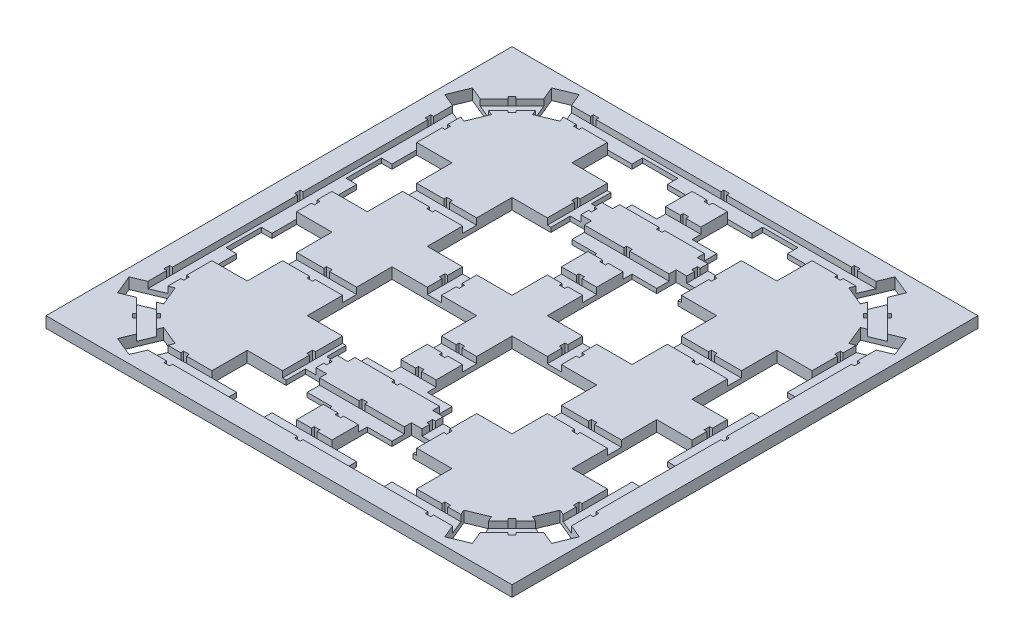
SolidWorks part; units mm, degrees
material "轻木"
ref_plane "前视基准面" through (0, 0, 0) normal (0, 0, 1) x (1, 0, 0)
ref_plane "上视基准面" through (0, 0, 0) normal (0, 1, 0) x (1, 0, 0)
ref_plane "右视基准面" through (0, 0, 0) normal (1, 0, 0) x (0, 0, -1)
sketch "草图1" plane through (0, 0, 0) normal (0, 1, 0) x (1, 0, 0)
  line L1 (-330, 330) -> (330, 330)
  line L2 (-330, 330) -> (-330, -330)
  line L3 (-330, -330) -> (330, -330)
  line L4 (330, 330) -> (330, -330)
  line L5 (-330, 330) -> (330, -330) construction
  line L6 (-330, -330) -> (330, 330) construction
  point P0 (0, 0)
  dimension "D1" = 660
  dimension "D2" = 660
extrude "凸台-拉伸1" add sketch "草图1" along normal blind 15.5
sketch "草图2" plane through (0, 15.5, 0) normal (0, 1, 0) x (1, 0, 0)
  line L0 (0, 0) -> (50000, 0) construction
  line L1 (-290, 290) -> (290, 290) construction
  line L2 (-290, 290) -> (-290, -290) construction
  line L3 (-290, -290) -> (290, -290) construction
  line L4 (290, 290) -> (290, -290) construction
  line L5 (-290, 290) -> (290, -290) construction
  line L6 (-290, -290) -> (290, 290) construction
  line L7 (0, 0) -> (0, 50000) construction
  line L8 (-290, 227.8579) -> (-227.8579, 290) construction
  line L9 (-280, 223.7157) -> (-280, 95)
  line L10 (-223.7157, 280) -> (-95, 280)
  line L11 (-280, 223.7157) -> (-223.7157, 280)
  line L12 (-300, 212) -> (-300, -232)
  line L13 (-212, 300) -> (212, 300)
  line L14 (-300, 232) -> (-232, 300)
  line L15 (-297.0711, 234.9289) -> (-234.9289, 297.0711) construction
  line L16 (-282.9289, 220.7868) -> (-220.7868, 282.9289) construction
  line L17 (280, 223.7157) -> (223.7157, 280)
  line L18 (300, 232) -> (232, 300)
  line L19 (280, 223.7157) -> (280, 95)
  line L20 (300, 212) -> (300, -232)
  line L21 (280, -223.7157) -> (223.7157, -280)
  line L22 (-300, 300) -> (290, 300) construction
  line L23 (-300, 300) -> (-300, -290) construction
  line L24 (-280, 280) -> (290, 280) construction
  line L25 (-280, 280) -> (-280, -290) construction
  line L26 (300, -232) -> (232, -300)
  line L27 (-232, -300) -> (232, -300)
  line L28 (-300, -232) -> (-232, -300)
  line L29 (-223.7157, -280) -> (-95, -280)
  line L30 (-280, -223.7157) -> (-223.7157, -280)
  line L31 (-95, 280) -> (-95, 95)
  line L32 (-75, 280) -> (-75, 242.5)
  line L33 (75, 280) -> (75, 242.5)
  line L34 (95, 280) -> (95, 95)
  line L35 (-280, -95) -> (-95, -95)
  line L36 (-280, -75) -> (-95, -75)
  line L37 (-280, 75) -> (-95, 75)
  line L38 (-280, 95) -> (-95, 95)
  line L39 (-75, 95) -> (75, 95)
  line L40 (-95, 75) -> (-95, -75)
  line L41 (-75, 75) -> (75, 75)
  line L42 (-75, 75) -> (-75, -75)
  line L43 (75, 75) -> (75, -75)
  line L44 (95, 95) -> (280, 95)
  line L45 (95, 75) -> (95, -75)
  line L46 (95, 75) -> (280, 75)
  line L47 (-75, -75) -> (75, -75)
  line L48 (-95, -95) -> (-95, -280)
  line L49 (-75, -95) -> (75, -95)
  line L50 (-75, -95) -> (-75, -132.5)
  line L51 (75, -95) -> (75, -132.5)
  line L52 (95, -75) -> (280, -75)
  line L53 (95, -95) -> (95, -280)
  line L54 (95, -95) -> (280, -95)
  line L55 (-75, 280) -> (75, 280)
  line L56 (95, 280) -> (223.7157, 280)
  line L57 (-280, 75) -> (-280, -75)
  line L58 (-280, -95) -> (-280, -223.7157)
  line L59 (-75, -280) -> (75, -280)
  line L60 (95, -280) -> (223.7157, -280)
  line L61 (280, -95) -> (280, -223.7157)
  line L62 (280, 75) -> (280, -75)
  line L63 (-75, 242.5) -> (75, 242.5)
  line L64 (-75, 212.5) -> (75, 212.5)
  line L65 (-75, 162.5) -> (75, 162.5)
  line L66 (-75, 132.5) -> (75, 132.5)
  line L67 (-75, -132.5) -> (75, -132.5)
  line L68 (-75, -162.5) -> (75, -162.5)
  line L69 (-75, -212.5) -> (75, -212.5)
  line L70 (-75, -242.5) -> (75, -242.5)
  line L71 (-75, -162.5) -> (-75, -212.5)
  line L72 (75, -162.5) -> (75, -212.5)
  line L73 (-75, -242.5) -> (-75, -280)
  line L74 (75, -242.5) -> (75, -280)
  line L75 (-75, 212.5) -> (-75, 162.5)
  line L76 (-75, 132.5) -> (-75, 95)
  line L77 (75, 212.5) -> (75, 162.5)
  line L78 (75, 132.5) -> (75, 95)
  line L79 (-212, 300) -> (-232, 300)
  line L80 (-300, 232) -> (-300, 212)
  line L81 (212, 300) -> (232, 300)
  line L82 (300, 232) -> (300, 212)
  arc A0 (-212, 300) -> (-232, 300) centre (-222, 300) ccw construction
  arc A1 (-300, 212) -> (-300, 232) centre (-300, 222) cw construction
  arc A2 (300, 212) -> (300, 232) centre (300, 222) ccw construction
  arc A3 (212, 300) -> (232, 300) centre (222, 300) cw construction
  circle A4 centre (-300, -222) radius 10 construction
  circle A5 centre (-222, -300) radius 10 construction
  circle A6 centre (300, -222) radius 10 construction
  circle A7 centre (222, -300) radius 10 construction
  point P0 (0, 0)
  dimension "D12" = 20
  dimension "D1" = 45
  dimension "D2" = 10
  dimension "D4" = 464
  dimension "D5" = 600
  dimension "D6" = 20
  dimension "D7" = 185
  dimension "D8" = 30
  dimension "D9" = 37.5
  dimension "D10" = 30
  dimension "D11" = 50
  dimension "D3" = 10
extrude "切除-拉伸1" cut sketch "草图2" against normal blind 9 contours L12 L28 L27 L26 L20 L18 L13 L14 L67 L50 L49 L51 L63 L32 L55 L33 L58 L35 L48 L29 L30 L57 L37 L40 L36 L47 L42 L41 L43 L38 L9 L11 L10 L31 L34 L56 L17 L19 L44 L54 L61 L21 L60 | A4 | A5 | A7 | A6
sketch "草图3" plane through (0, 15.5, 0) normal (0, 1, 0) x (1, 0, 0)
  line L0 (-593.6882, 0) -> (581.5427, 0) construction
  line L1 (0, 531.2049) -> (0, -386.0529) construction
  line L2 (-232, 300) -> (-223.7157, 280) construction
  line L3 (-266, 266) -> (0, 0) construction
  line L4 (-300, 232) -> (-232, 300) construction
  line L5 (-251.2831, 307.3567) -> (-232.149, 261.1628)
  line L6 (-251.2831, 307.3567) -> (-223.5668, 318.8372)
  line L7 (-232.149, 261.1628) -> (-204.4326, 272.6433)
  line L8 (-223.5668, 318.8372) -> (-204.4326, 272.6433)
  line L9 (-251.2831, 307.3567) -> (-204.4326, 272.6433) construction
  line L10 (-232.149, 261.1628) -> (-223.5668, 318.8372) construction
  line L11 (-95, 280) -> (-75, 280) construction
  line L12 (-95, 95) -> (-75, 95) construction
  line L13 (-110, 295) -> (-60, 295)
  line L14 (-110, 295) -> (-110, 265)
  line L15 (-110, 265) -> (-60, 265)
  line L16 (-60, 295) -> (-60, 265)
  line L17 (-110, 295) -> (-60, 265) construction
  line L18 (-110, 265) -> (-60, 295) construction
  line L19 (-75, 132.5) -> (-75, 95) construction
  line L20 (-85, 95) -> (-85, 85) construction
  line L21 (-265, 110) -> (-265, 60)
  line L22 (-110, 110) -> (-60, 110)
  line L23 (-110, 110) -> (-110, 60)
  line L24 (-110, 60) -> (-60, 60)
  line L25 (-60, 110) -> (-60, 60)
  line L26 (-110, 110) -> (-60, 60) construction
  line L27 (-110, 60) -> (-60, 110) construction
  line L28 (-295, 60) -> (-265, 60)
  line L29 (-295, 110) -> (-295, 60)
  line L30 (-295, 110) -> (-265, 110)
  line L31 (-261.1628, 232.149) -> (-272.6433, 204.4326)
  line L32 (-318.8372, 223.5668) -> (-272.6433, 204.4326)
  line L33 (-307.3567, 251.2831) -> (-318.8372, 223.5668)
  line L34 (-307.3567, 251.2831) -> (-261.1628, 232.149)
  line L35 (110, 60) -> (60, 60)
  line L36 (60, 110) -> (60, 60)
  line L37 (110, 110) -> (60, 110)
  line L38 (110, 110) -> (110, 60)
  line L39 (110, 265) -> (60, 265)
  line L40 (60, 295) -> (60, 265)
  line L41 (110, 295) -> (60, 295)
  line L42 (110, 295) -> (110, 265)
  line L43 (232.149, 261.1628) -> (204.4326, 272.6433)
  line L44 (223.5668, 318.8372) -> (204.4326, 272.6433)
  line L45 (251.2831, 307.3567) -> (223.5668, 318.8372)
  line L46 (251.2831, 307.3567) -> (232.149, 261.1628)
  line L47 (307.3567, 251.2831) -> (261.1628, 232.149)
  line L48 (307.3567, 251.2831) -> (318.8372, 223.5668)
  line L49 (318.8372, 223.5668) -> (272.6433, 204.4326)
  line L50 (261.1628, 232.149) -> (272.6433, 204.4326)
  line L51 (295, 110) -> (265, 110)
  line L52 (295, 110) -> (295, 60)
  line L53 (295, 60) -> (265, 60)
  line L54 (265, 110) -> (265, 60)
  line L55 (-110, -60) -> (-60, -110) construction
  line L56 (-110, -110) -> (-60, -60) construction
  line L57 (-85, -95) -> (-85, -85) construction
  line L58 (-110, -265) -> (-60, -295) construction
  line L59 (-110, -295) -> (-60, -265) construction
  line L60 (-95, -95) -> (-75, -95) construction
  line L61 (-95, -280) -> (-75, -280) construction
  line L62 (-232.149, -261.1628) -> (-223.5668, -318.8372) construction
  line L63 (-251.2831, -307.3567) -> (-204.4326, -272.6433) construction
  line L64 (-232, -300) -> (-223.7157, -280) construction
  line L65 (265, -110) -> (265, -60)
  line L66 (295, -60) -> (265, -60)
  line L67 (295, -110) -> (295, -60)
  line L68 (295, -110) -> (265, -110)
  line L69 (261.1628, -232.149) -> (272.6433, -204.4326)
  line L70 (318.8372, -223.5668) -> (272.6433, -204.4326)
  line L71 (307.3567, -251.2831) -> (318.8372, -223.5668)
  line L72 (307.3567, -251.2831) -> (261.1628, -232.149)
  line L73 (251.2831, -307.3567) -> (232.149, -261.1628)
  line L74 (251.2831, -307.3567) -> (223.5668, -318.8372)
  line L75 (223.5668, -318.8372) -> (204.4326, -272.6433)
  line L76 (232.149, -261.1628) -> (204.4326, -272.6433)
  line L77 (110, -295) -> (110, -265)
  line L78 (110, -295) -> (60, -295)
  line L79 (60, -295) -> (60, -265)
  line L80 (110, -265) -> (60, -265)
  line L81 (110, -110) -> (110, -60)
  line L82 (110, -110) -> (60, -110)
  line L83 (60, -110) -> (60, -60)
  line L84 (110, -60) -> (60, -60)
  line L85 (-307.3567, -251.2831) -> (-261.1628, -232.149)
  line L86 (-307.3567, -251.2831) -> (-318.8372, -223.5668)
  line L87 (-318.8372, -223.5668) -> (-272.6433, -204.4326)
  line L88 (-261.1628, -232.149) -> (-272.6433, -204.4326)
  line L89 (-295, -110) -> (-265, -110)
  line L90 (-295, -110) -> (-295, -60)
  line L91 (-295, -60) -> (-265, -60)
  line L92 (-60, -110) -> (-60, -60)
  line L93 (-110, -60) -> (-60, -60)
  line L94 (-110, -110) -> (-110, -60)
  line L95 (-110, -110) -> (-60, -110)
  line L96 (-265, -110) -> (-265, -60)
  line L97 (-60, -295) -> (-60, -265)
  line L98 (-110, -265) -> (-60, -265)
  line L99 (-110, -295) -> (-110, -265)
  line L100 (-110, -295) -> (-60, -295)
  line L101 (-223.5668, -318.8372) -> (-204.4326, -272.6433)
  line L102 (-232.149, -261.1628) -> (-204.4326, -272.6433)
  line L103 (-251.2831, -307.3567) -> (-223.5668, -318.8372)
  line L104 (-251.2831, -307.3567) -> (-232.149, -261.1628)
  line L105 (-75, 242.5) -> (-75, 212.5) construction
  line L106 (90, 202.5) -> (60, 202.5)
  line L107 (-90, 252.5) -> (-60, 252.5)
  line L108 (-90, 252.5) -> (-90, 202.5)
  line L109 (-90, 202.5) -> (-60, 202.5)
  line L110 (-60, 252.5) -> (-60, 202.5)
  line L111 (-90, 252.5) -> (-60, 202.5) construction
  line L112 (-90, 202.5) -> (-60, 252.5) construction
  line L113 (60, 252.5) -> (60, 202.5)
  line L114 (90, 252.5) -> (60, 252.5)
  line L115 (90, 252.5) -> (90, 202.5)
  line L116 (90, -252.5) -> (90, -202.5)
  line L117 (90, -252.5) -> (60, -252.5)
  line L118 (60, -252.5) -> (60, -202.5)
  line L119 (90, -202.5) -> (60, -202.5)
  line L120 (-90, -202.5) -> (-60, -202.5)
  line L121 (-60, -252.5) -> (-60, -202.5)
  line L122 (-90, -252.5) -> (-60, -252.5)
  line L123 (-90, -252.5) -> (-90, -202.5)
  line L124 (-75, 187.5) -> (75, 187.5) construction
  line L125 (-75, 212.5) -> (-75, 162.5) construction
  line L126 (75, 212.5) -> (75, 162.5) construction
  line L127 (90, 122.5) -> (90, 172.5)
  line L128 (90, 122.5) -> (60, 122.5)
  line L129 (60, 122.5) -> (60, 172.5)
  line L130 (90, 172.5) -> (60, 172.5)
  line L131 (-90, 172.5) -> (-60, 172.5)
  line L132 (-60, 122.5) -> (-60, 172.5)
  line L133 (-90, 122.5) -> (-60, 122.5)
  line L134 (-90, 122.5) -> (-90, 172.5)
  line L135 (90, -122.5) -> (60, -122.5)
  line L136 (60, -122.5) -> (60, -172.5)
  line L137 (90, -172.5) -> (60, -172.5)
  line L138 (90, -122.5) -> (90, -172.5)
  line L139 (-90, -122.5) -> (-90, -172.5)
  line L140 (-90, -122.5) -> (-60, -122.5)
  line L141 (-60, -122.5) -> (-60, -172.5)
  line L142 (-90, -172.5) -> (-60, -172.5)
  point P13 (-85, 280)
  point P14 (-227.8579, 290)
  point P15 (-227.8579, 290)
  point P119 (-75, 227.5)
  dimension "D1" = 30
  dimension "D2" = 50
  dimension "D3" = 30
  dimension "D4" = 50
  dimension "D5" = 50
  dimension "D6" = 50
extrude "切除-拉伸2" cut sketch "草图3" against normal through all
sketch "草图4" plane through (0, 15.5, 0) normal (0, 1, 0) x (1, 0, 0)
  line L0 (0, 300) -> (0, -330) construction
  line L1 (-215.7641, 300) -> (215.7641, 300) construction
  line L2 (-330, -330) -> (330, -330) construction
  line L3 (-265, 95) -> (-265, 75) construction
  line L4 (-265, 85) -> (-56.1842, 85) construction
  line L5 (-95, 110) -> (-75, 110) construction
  line L6 (-85, 110) -> (-85, 46.2391) construction
  line L8 (0, 0) -> (-330, 330) construction
  line L9 (330, 330) -> (-330, 330) construction
  line L12 (-280, 60) -> (-280, -60) construction
  line L17 (-280, 145) -> (-230, 145)
  line L18 (-330, 330) -> (-330, -330) construction
  line L19 (-280, 145) -> (-280, 25)
  line L24 (-280, 25) -> (-230, 25)
  line L81 (-230, 145) -> (-230, 25)
  line L82 (-280, 145) -> (-230, 25) construction
  line L147 (-280, 25) -> (-230, 145) construction
  line L152 (-25, 280) -> (-25, 230)
  line L153 (75, 187.5) -> (-110, 187.5) construction
  line L154 (75, 202.5) -> (75, 172.5) construction
  line L155 (-145, 145) -> (-25, 145)
  line L156 (-145, 145) -> (-145, 25)
  line L157 (-145, 25) -> (-25, 25)
  line L158 (-25, 145) -> (-25, 25)
  line L159 (-145, 145) -> (-25, 25) construction
  line L160 (-145, 25) -> (-25, 145) construction
  line L161 (-145, 230) -> (-25, 230)
  line L162 (-145, 280) -> (-145, 230)
  line L163 (-145, 280) -> (-25, 280)
  line L164 (25, 145) -> (25, 25)
  line L165 (145, 25) -> (25, 25)
  line L166 (145, 145) -> (145, 25)
  line L167 (145, 145) -> (25, 145)
  line L168 (145, 280) -> (25, 280)
  line L169 (145, 280) -> (145, 230)
  line L170 (145, 230) -> (25, 230)
  line L171 (25, 280) -> (25, 230)
  line L172 (280, 25) -> (230, 25)
  line L173 (230, 145) -> (230, 25)
  line L174 (280, 145) -> (230, 145)
  line L175 (280, 145) -> (280, 25)
  line L176 (-420.0546, 0) -> (403.8236, 0) construction
  line L177 (-145, -25) -> (-25, -145) construction
  line L178 (-145, -145) -> (-25, -25) construction
  line L179 (75, -187.5) -> (-110, -187.5) construction
  line L180 (-280, -25) -> (-230, -145) construction
  line L181 (-280, -145) -> (-230, -25) construction
  line L182 (-85, -110) -> (-85, -46.2391) construction
  line L183 (-95, -110) -> (-75, -110) construction
  line L184 (-265, -85) -> (-56.1842, -85) construction
  line L185 (-265, -95) -> (-265, -75) construction
  line L186 (280, -145) -> (280, -25)
  line L187 (280, -145) -> (230, -145)
  line L188 (230, -145) -> (230, -25)
  line L189 (280, -25) -> (230, -25)
  line L190 (25, -280) -> (25, -230)
  line L191 (145, -230) -> (25, -230)
  line L192 (145, -280) -> (145, -230)
  line L193 (145, -280) -> (25, -280)
  line L194 (145, -145) -> (25, -145)
  line L195 (145, -145) -> (145, -25)
  line L196 (145, -25) -> (25, -25)
  line L197 (25, -145) -> (25, -25)
  line L198 (-145, -280) -> (-25, -280)
  line L199 (-145, -280) -> (-145, -230)
  line L200 (-145, -230) -> (-25, -230)
  line L201 (-25, -145) -> (-25, -25)
  line L202 (-145, -25) -> (-25, -25)
  line L203 (-145, -145) -> (-145, -25)
  line L204 (-145, -145) -> (-25, -145)
  line L205 (-25, -280) -> (-25, -230)
  line L206 (-230, -145) -> (-230, -25)
  line L207 (-280, -25) -> (-230, -25)
  line L208 (-280, -145) -> (-280, -25)
  line L209 (-280, -145) -> (-230, -145)
  point P14 (-255, 85)
  point P27 (-85, 85)
  point P84 (-85, -85)
  point P85 (-255, -85)
  dimension "D1" = 50
  dimension "D2" = 120
  dimension "D3" = 120
extrude "切除-拉伸3" cut sketch "草图4" against normal through all
sketch "草图6" plane through (0, 15.5, 0) normal (0, 1, 0) x (1, 0, 0)
  line L0 (0, -330) -> (0, 330) construction
  line L1 (-330, -330) -> (330, -330) construction
  line L2 (330, 330) -> (-330, 330) construction
  line L3 (330, 0) -> (-330, 0) construction
  line L4 (330, -330) -> (330, 330) construction
  line L5 (-330, 330) -> (-330, -330) construction
  line L6 (330, -330) -> (0, 0) construction
  line L7 (280, -145) -> (280, -207.4798) construction
  line L8 (276, -189) -> (280, -189)
  line L9 (276, -189) -> (276, -181)
  line L10 (276, -181) -> (280, -181)
  line L11 (280, -189) -> (280, -181)
  line L12 (276, -189) -> (280, -181) construction
  line L13 (276, -181) -> (280, -189) construction
  line L14 (230, -145) -> (280, -145) construction
  line L15 (300, -189) -> (300, -181)
  line L16 (300, -189) -> (304, -189)
  line L17 (304, -189) -> (304, -181)
  line L18 (300, -181) -> (304, -181)
  line L19 (300, -4) -> (300, 4)
  line L20 (300, -4) -> (304, -4)
  line L21 (304, -4) -> (304, 4)
  line L22 (300, 4) -> (304, 4)
  line L23 (300, 181) -> (300, 189)
  line L24 (300, 181) -> (304, 181)
  line L25 (304, 181) -> (304, 189)
  line L26 (300, 189) -> (304, 189)
  line L27 (276, -4) -> (276, 4)
  line L28 (276, -4) -> (280, -4)
  line L29 (280, -4) -> (280, 4)
  line L30 (276, 4) -> (280, 4)
  line L31 (276, 181) -> (276, 189)
  line L32 (276, 181) -> (280, 181)
  line L33 (280, 181) -> (280, 189)
  line L34 (276, 189) -> (280, 189)
  line L35 (276, -189) -> (300, -189) construction
  line L36 (249.0294, -254.6863) -> (254.6863, -249.0294)
  line L37 (268.5195, -235.1962) -> (235.1962, -268.5195) construction
  line L38 (254.6863, -249.0294) -> (251.8579, -246.201)
  line L39 (251.8579, -246.201) -> (246.201, -251.8579)
  line L40 (249.0294, -254.6863) -> (246.201, -251.8579)
  line L41 (268.8284, -263.1716) -> (271.6569, -266)
  line L42 (288.5195, -243.4805) -> (243.4805, -288.5195) construction
  line L43 (271.6569, -266) -> (266, -271.6569)
  line L44 (263.1716, -268.8284) -> (268.8284, -263.1716)
  line L45 (263.1716, -268.8284) -> (266, -271.6569)
  line L46 (189, -276) -> (189, -300) construction
  line L47 (181, -276) -> (189, -280) construction
  line L48 (189, -276) -> (181, -280) construction
  line L49 (-189, -276) -> (-189, -280)
  line L50 (-181, -280) -> (-189, -280)
  line L51 (-181, -276) -> (-181, -280)
  line L52 (-181, -276) -> (-189, -276)
  line L53 (-4, -276) -> (-4, -280)
  line L54 (4, -280) -> (-4, -280)
  line L55 (4, -276) -> (4, -280)
  line L56 (4, -276) -> (-4, -276)
  line L57 (-189, -300) -> (-189, -304)
  line L58 (-181, -304) -> (-189, -304)
  line L59 (-181, -300) -> (-181, -304)
  line L60 (-181, -300) -> (-189, -300)
  line L61 (-4, -300) -> (-4, -304)
  line L62 (4, -304) -> (-4, -304)
  line L63 (4, -300) -> (4, -304)
  line L64 (4, -300) -> (-4, -300)
  line L65 (181, -300) -> (181, -304)
  line L66 (189, -304) -> (181, -304)
  line L67 (189, -300) -> (189, -304)
  line L68 (189, -300) -> (181, -300)
  line L69 (189, -280) -> (181, -280)
  line L70 (181, -276) -> (181, -280)
  line L71 (189, -276) -> (181, -276)
  line L72 (189, -276) -> (189, -280)
  line L73 (-276, -189) -> (-300, -189) construction
  line L74 (-276, -181) -> (-280, -189) construction
  line L75 (-276, -189) -> (-280, -181) construction
  line L76 (-276, 4) -> (-280, 4)
  line L77 (-280, -4) -> (-280, 4)
  line L78 (-276, -4) -> (-280, -4)
  line L79 (-276, -4) -> (-276, 4)
  line L80 (-300, 4) -> (-304, 4)
  line L81 (-304, -4) -> (-304, 4)
  line L82 (-300, -4) -> (-304, -4)
  line L83 (-300, -4) -> (-300, 4)
  line L84 (-300, -181) -> (-304, -181)
  line L85 (-304, -189) -> (-304, -181)
  line L86 (-300, -189) -> (-304, -189)
  line L87 (-300, -189) -> (-300, -181)
  line L88 (-280, -189) -> (-280, -181)
  line L89 (-276, -181) -> (-280, -181)
  line L90 (-276, -189) -> (-276, -181)
  line L91 (-276, -189) -> (-280, -189)
  line L92 (263.1716, 268.8284) -> (266, 271.6569)
  line L93 (263.1716, 268.8284) -> (268.8284, 263.1716)
  line L94 (271.6569, 266) -> (266, 271.6569)
  line L95 (268.8284, 263.1716) -> (271.6569, 266)
  line L96 (249.0294, 254.6863) -> (246.201, 251.8579)
  line L97 (251.8579, 246.201) -> (246.201, 251.8579)
  line L98 (254.6863, 249.0294) -> (251.8579, 246.201)
  line L99 (249.0294, 254.6863) -> (254.6863, 249.0294)
  line L100 (-276, 189) -> (-280, 181) construction
  line L101 (-276, 181) -> (-280, 189) construction
  line L102 (-276, 189) -> (-300, 189) construction
  line L103 (189, 276) -> (181, 280) construction
  line L104 (181, 276) -> (189, 280) construction
  line L105 (189, 276) -> (189, 300) construction
  line L106 (-276, 189) -> (-280, 189)
  line L107 (-276, 189) -> (-276, 181)
  line L108 (-276, 181) -> (-280, 181)
  line L109 (-280, 189) -> (-280, 181)
  line L110 (-300, 189) -> (-300, 181)
  line L111 (-300, 189) -> (-304, 189)
  line L112 (-304, 189) -> (-304, 181)
  line L113 (-300, 181) -> (-304, 181)
  line L114 (-300, 4) -> (-304, 4)
  line L115 (-300, -4) -> (-304, -4)
  line L116 (-276, 4) -> (-280, 4)
  line L117 (-276, -4) -> (-280, -4)
  line L118 (189, 276) -> (189, 280)
  line L119 (189, 276) -> (181, 276)
  line L120 (181, 276) -> (181, 280)
  line L121 (189, 280) -> (181, 280)
  line L122 (189, 300) -> (181, 300)
  line L123 (189, 300) -> (189, 304)
  line L124 (189, 304) -> (181, 304)
  line L125 (181, 300) -> (181, 304)
  line L126 (4, 300) -> (-4, 300)
  line L127 (4, 300) -> (4, 304)
  line L128 (4, 304) -> (-4, 304)
  line L129 (-4, 300) -> (-4, 304)
  line L130 (-181, 300) -> (-189, 300)
  line L131 (-181, 300) -> (-181, 304)
  line L132 (-181, 304) -> (-189, 304)
  line L133 (-189, 300) -> (-189, 304)
  line L134 (4, 276) -> (-4, 276)
  line L135 (4, 276) -> (4, 280)
  line L136 (4, 280) -> (-4, 280)
  line L137 (-4, 276) -> (-4, 280)
  line L138 (-181, 276) -> (-189, 276)
  line L139 (-181, 276) -> (-181, 280)
  line L140 (-181, 280) -> (-189, 280)
  line L141 (-189, 276) -> (-189, 280)
  line L142 (187.5, -95) -> (187.5, -125.6774) construction
  line L143 (145, -95) -> (230, -95) construction
  line L144 (230, -95) -> (230, -75) construction
  line L145 (191.5, -99) -> (183.5, -99)
  line L146 (191.5, -99) -> (191.5, -95)
  line L147 (191.5, -95) -> (183.5, -95)
  line L148 (183.5, -99) -> (183.5, -95)
  line L149 (191.5, -99) -> (183.5, -95) construction
  line L150 (191.5, -95) -> (183.5, -99) construction
  line L151 (230, -85) -> (132.4657, -85) construction
  line L152 (191.5, -75) -> (183.5, -75)
  line L153 (183.5, -71) -> (183.5, -75)
  line L154 (191.5, -71) -> (183.5, -71)
  line L155 (191.5, -71) -> (191.5, -75)
  line L156 (4, -99) -> (4, -95)
  line L157 (4, -99) -> (-4, -99)
  line L158 (-4, -99) -> (-4, -95)
  line L159 (4, -95) -> (-4, -95)
  line L160 (4, -75) -> (-4, -75)
  line L161 (-4, -71) -> (-4, -75)
  line L162 (4, -71) -> (-4, -71)
  line L163 (4, -71) -> (4, -75)
  line L164 (-183.5, -99) -> (-183.5, -95)
  line L165 (-183.5, -99) -> (-191.5, -99)
  line L166 (-191.5, -99) -> (-191.5, -95)
  line L167 (-183.5, -95) -> (-191.5, -95)
  line L168 (-183.5, -75) -> (-191.5, -75)
  line L169 (-191.5, -71) -> (-191.5, -75)
  line L170 (-183.5, -71) -> (-191.5, -71)
  line L171 (-183.5, -71) -> (-183.5, -75)
  line L172 (4, 71) -> (4, 75)
  line L173 (4, 71) -> (-4, 71)
  line L174 (-4, 71) -> (-4, 75)
  line L175 (4, 75) -> (-4, 75)
  line L176 (4, 95) -> (-4, 95)
  line L177 (-4, 99) -> (-4, 95)
  line L178 (4, 99) -> (-4, 99)
  line L179 (4, 99) -> (4, 95)
  line L180 (-183.5, 71) -> (-183.5, 75)
  line L181 (-183.5, 71) -> (-191.5, 71)
  line L182 (-191.5, 71) -> (-191.5, 75)
  line L183 (-183.5, 75) -> (-191.5, 75)
  line L184 (-183.5, 95) -> (-191.5, 95)
  line L185 (-191.5, 99) -> (-191.5, 95)
  line L186 (-183.5, 99) -> (-191.5, 99)
  line L187 (-183.5, 99) -> (-183.5, 95)
  line L188 (191.5, 71) -> (191.5, 75)
  line L189 (191.5, 71) -> (183.5, 71)
  line L190 (183.5, 71) -> (183.5, 75)
  line L191 (191.5, 75) -> (183.5, 75)
  line L192 (191.5, 95) -> (183.5, 95)
  line L193 (183.5, 99) -> (183.5, 95)
  line L194 (191.5, 99) -> (183.5, 99)
  line L195 (191.5, 99) -> (191.5, 95)
  line L196 (145, 75) -> (230, 75) construction
  line L197 (95, -191.5) -> (99, -183.5) construction
  line L198 (99, -191.5) -> (95, -183.5) construction
  line L199 (-99, -191.5) -> (-95, -191.5)
  line L200 (-99, -191.5) -> (-99, -183.5)
  line L201 (-99, -183.5) -> (-95, -183.5)
  line L202 (-95, -191.5) -> (-95, -183.5)
  line L203 (-75, -191.5) -> (-75, -183.5)
  line L204 (-71, -183.5) -> (-75, -183.5)
  line L205 (-71, -191.5) -> (-71, -183.5)
  line L206 (-71, -191.5) -> (-75, -191.5)
  line L207 (-99, 183.5) -> (-95, 183.5)
  line L208 (-99, 183.5) -> (-99, 191.5)
  line L209 (-99, 191.5) -> (-95, 191.5)
  line L210 (-95, 183.5) -> (-95, 191.5)
  line L211 (-75, 183.5) -> (-75, 191.5)
  line L212 (-71, 191.5) -> (-75, 191.5)
  line L213 (-71, 183.5) -> (-71, 191.5)
  line L214 (-71, 183.5) -> (-75, 183.5)
  line L215 (-99, -4) -> (-95, -4)
  line L216 (-99, -4) -> (-99, 4)
  line L217 (-99, 4) -> (-95, 4)
  line L218 (-95, -4) -> (-95, 4)
  line L219 (-75, -4) -> (-75, 4)
  line L220 (-71, 4) -> (-75, 4)
  line L221 (-71, -4) -> (-71, 4)
  line L222 (-71, -4) -> (-75, -4)
  line L223 (71, 183.5) -> (75, 183.5)
  line L224 (71, 183.5) -> (71, 191.5)
  line L225 (71, 191.5) -> (75, 191.5)
  line L226 (75, 183.5) -> (75, 191.5)
  line L227 (95, 183.5) -> (95, 191.5)
  line L228 (99, 191.5) -> (95, 191.5)
  line L229 (99, 183.5) -> (99, 191.5)
  line L230 (99, 183.5) -> (95, 183.5)
  line L231 (71, -4) -> (75, -4)
  line L232 (71, -4) -> (71, 4)
  line L233 (71, 4) -> (75, 4)
  line L234 (75, -4) -> (75, 4)
  line L235 (95, -4) -> (95, 4)
  line L236 (99, 4) -> (95, 4)
  line L237 (99, -4) -> (99, 4)
  line L238 (99, -4) -> (95, -4)
  line L239 (71, -191.5) -> (75, -191.5)
  line L240 (71, -191.5) -> (71, -183.5)
  line L241 (71, -183.5) -> (75, -183.5)
  line L242 (75, -191.5) -> (75, -183.5)
  line L243 (99, -183.5) -> (95, -183.5)
  line L244 (95, -191.5) -> (95, -183.5)
  line L245 (99, -191.5) -> (95, -191.5)
  line L246 (99, -191.5) -> (99, -183.5)
  line L247 (-25, -242.5) -> (25, -242.5) construction
  line L248 (4, -246.5) -> (-4, -246.5)
  line L249 (4, -246.5) -> (4, -242.5)
  line L250 (4, -242.5) -> (-4, -242.5)
  line L251 (-4, -246.5) -> (-4, -242.5)
  line L252 (4, -246.5) -> (-4, -242.5) construction
  line L253 (4, -242.5) -> (-4, -246.5) construction
  line L254 (-60, -212.5) -> (60, -212.5) construction
  line L255 (4, -208.5) -> (-4, -208.5)
  line L256 (4, -208.5) -> (4, -212.5)
  line L257 (4, -212.5) -> (-4, -212.5)
  line L258 (-4, -208.5) -> (-4, -212.5)
  line L259 (4, -208.5) -> (-4, -212.5) construction
  line L260 (4, -212.5) -> (-4, -208.5) construction
  line L261 (-60, -162.5) -> (60, -162.5) construction
  line L262 (4, -166.5) -> (-4, -166.5)
  line L263 (4, -166.5) -> (4, -162.5)
  line L264 (4, -162.5) -> (-4, -162.5)
  line L265 (-4, -166.5) -> (-4, -162.5)
  line L266 (4, -166.5) -> (-4, -162.5) construction
  line L267 (4, -162.5) -> (-4, -166.5) construction
  line L268 (-25, -132.5) -> (25, -132.5) construction
  line L269 (4, -128.5) -> (-4, -128.5)
  line L270 (4, -128.5) -> (4, -132.5)
  line L271 (4, -132.5) -> (-4, -132.5)
  line L272 (-4, -128.5) -> (-4, -132.5)
  line L273 (4, -128.5) -> (-4, -132.5) construction
  line L274 (4, -132.5) -> (-4, -128.5) construction
  line L275 (4, 132.5) -> (-4, 132.5)
  line L276 (-4, 128.5) -> (-4, 132.5)
  line L277 (4, 128.5) -> (-4, 128.5)
  line L278 (4, 128.5) -> (4, 132.5)
  line L279 (4, 162.5) -> (-4, 162.5)
  line L280 (-4, 166.5) -> (-4, 162.5)
  line L281 (4, 166.5) -> (-4, 166.5)
  line L282 (4, 166.5) -> (4, 162.5)
  line L283 (4, 212.5) -> (-4, 212.5)
  line L284 (-4, 208.5) -> (-4, 212.5)
  line L285 (4, 208.5) -> (-4, 208.5)
  line L286 (4, 208.5) -> (4, 212.5)
  line L287 (4, 242.5) -> (-4, 242.5)
  line L288 (-4, 246.5) -> (-4, 242.5)
  line L289 (4, 246.5) -> (-4, 246.5)
  line L290 (4, 246.5) -> (4, 242.5)
  line L291 (-263.1716, 268.8284) -> (-268.8284, 263.1716)
  line L292 (-268.8284, 263.1716) -> (-271.6569, 266)
  line L293 (-271.6569, 266) -> (-266, 271.6569)
  line L294 (-263.1716, 268.8284) -> (-266, 271.6569)
  line L295 (-249.0294, 254.6863) -> (-254.6863, 249.0294)
  line L296 (-254.6863, 249.0294) -> (-251.8579, 246.201)
  line L297 (-251.8579, 246.201) -> (-246.201, 251.8579)
  line L298 (-249.0294, 254.6863) -> (-246.201, 251.8579)
  line L299 (-254.6863, -249.0294) -> (-251.8579, -246.201)
  line L300 (-249.0294, -254.6863) -> (-254.6863, -249.0294)
  line L301 (-249.0294, -254.6863) -> (-246.201, -251.8579)
  line L302 (-251.8579, -246.201) -> (-246.201, -251.8579)
  line L303 (-268.8284, -263.1716) -> (-271.6569, -266)
  line L304 (-263.1716, -268.8284) -> (-268.8284, -263.1716)
  line L305 (-263.1716, -268.8284) -> (-266, -271.6569)
  line L306 (-271.6569, -266) -> (-266, -271.6569)
  point P16 (278, -185)
  point P54 (249.0294, -249.0294)
  point P55 (251.8579, -251.8579)
  point P62 (268.8284, -268.8284)
  point P63 (266, -266)
  point P87 (185, -278)
  point P104 (-278, -185)
  point P113 (266, 266)
  point P114 (268.8284, 268.8284)
  point P115 (251.8579, 251.8579)
  point P116 (249.0294, 249.0294)
  point P149 (-278, 185)
  point P150 (185, 278)
  point P155 (187.5, -97)
  point P260 (97, -187.5)
  point P261 (0, -244.5)
  point P268 (0, -210.5)
  point P275 (0, -164.5)
  point P282 (0, -130.5)
  line M54 (-25, -75) -> (25, -75)
  line M57 (75, -25) -> (75, 25)
  line M60 (25, 75) -> (-25, 75)
  line M63 (-75, 25) -> (-75, -25)
  dimension "D1" = 4
  dimension "D2" = 8
  dimension "D3" = 40
  dimension "D6" = 24
  dimension "D7" = 4
  dimension "D8" = 8
  dimension "D9" = 4
  dimension "D10" = 8
  dimension "D11" = 3
  dimension "D4" = 2
  dimension "D5" = 3
  dimension "D12" = 2
extrude "切除-拉伸4" cut sketch "草图6" against normal through all contours L67 L68 L65 L66 | L8 L11 L10 L9 | L63 L64 L61 L62 | L55 L56 L53 L54 | L59 L60 L57 L58 | L51 L52 L49 L50 | L302 L299 L300 L301 | L303 L306 L305 L304 | L86 L87 L84 L85 | L199 L202 L201 L200 | L255 L258 L257 L256 | L265 L262 L263 L264 | L239 L242 L241 L240 | L245 L246 L243 L244 | L148 L145 L146 L147 | L155 L154 L153 L152 | L269 L272 L271 L270 | L156 L159 L158 L157 | L163 L162 L161 M54 | L164 L167 L166 L165 | L171 L170 L169 L168 | L22 L19 L20 L21 | L30 L27 L28 L29 | L238 L237 L236 L235 | L233 L232 L231 M57 | L222 L221 L220 M63 | L215 L218 L217 L216 | L78 L79 L76 L77 | L82 L83 L80 L81 | L188 L191 L190 L189 | L195 L194 L193 L192 | L174 L173 L172 M60 | L179 L178 L177 L176 | L180 L183 L182 L181 | L187 L186 L185 L184 | L277 L278 L275 L276 | L26 L23 L24 L25 | L34 L31 L32 L33 | L93 L95 L94 L92 | L99 L96 L97 L98 | L118 L121 L120 L119 | L125 L122 L123 L124 | L230 L229 L228 L227 | L223 L226 L225 L224 | L285 L286 L283 L284 | L137 L134 L135 L136 | L129 L126 L127 L128 | L214 L213 L212 L211 | L207 L210 L209 L208 | L141 L138 L139 L140 | L133 L130 L131 L132 | L298 L295 L296 L297 | L291 L294 L293 L292 | L113 L110 L111 L112 | L106 L109 L108 L107 | L69 L70 L71 L72 | L41 L43 L45 L44 | L40 L39 L38 L36 | L15 L18 L17 L16 | L249 L250 L251 L248 | L90 L89 L88 L91 | L203 L204 L205 L206 | L280 L279 L282 L281 | L287 L288 L289 L290
